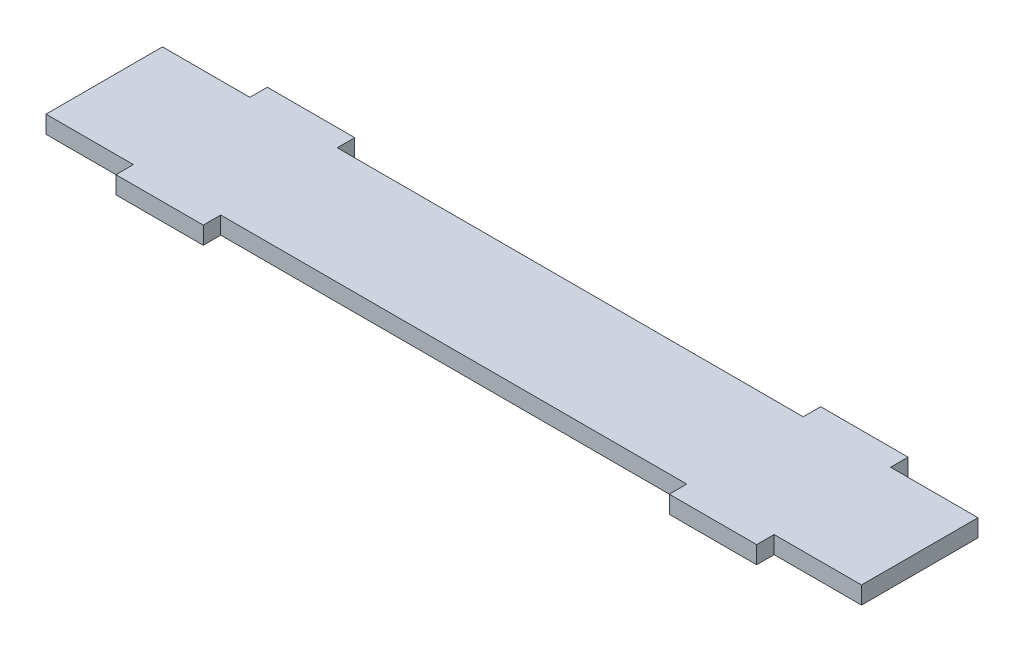
SolidWorks part; units mm, degrees
ref_plane "前视基准面" through (0, 0, 0) normal (0, 0, 1) x (1, 0, 0)
ref_plane "上视基准面" through (0, 0, 0) normal (0, 1, 0) x (1, 0, 0)
ref_plane "右视基准面" through (0, 0, 0) normal (1, 0, 0) x (0, 0, -1)
other "Configuration Table"
sketch "草图1" plane through (0, 0, 0) normal (0, 1, 0) x (1, 0, 0)
  line L0 (0, 16.6337) -> (0, -14.7525) construction
  line L1 (-70, 10) -> (70, 10)
  line L2 (-70, 10) -> (-70, -10)
  line L3 (-70, -10) -> (70, -10)
  line L4 (70, 10) -> (70, -10)
  line L5 (-70, 10) -> (70, -10) construction
  line L6 (-70, -10) -> (70, 10) construction
  line L7 (-55, 10) -> (-40, 10)
  line L8 (-55, 10) -> (-55, 13)
  line L9 (-55, 13) -> (-40, 13)
  line L10 (-40, 10) -> (-40, 13)
  line L11 (40, 10) -> (40, 13)
  line L12 (55, 13) -> (40, 13)
  line L13 (55, 10) -> (55, 13)
  line L14 (55, 10) -> (40, 10)
  line L15 (-70, 0) -> (-35.2475, 0) construction
  line L16 (55, -10) -> (40, -10)
  line L17 (55, -10) -> (55, -13)
  line L18 (55, -13) -> (40, -13)
  line L19 (40, -10) -> (40, -13)
  line L20 (-40, -10) -> (-40, -13)
  line L21 (-55, -13) -> (-40, -13)
  line L22 (-55, -10) -> (-55, -13)
  line L23 (-55, -10) -> (-40, -10)
  point P0 (0, 0)
  dimension "D1" = 20
  dimension "D2" = 140
  dimension "D3" = 3
  dimension "D4" = 15
  dimension "D5" = 40
extrude "凸台-拉伸1" add sketch "草图1" along normal blind 3 contours L4 L1 L2 L3 | L1 L10 L9 L8 | L3 L22 L21 L20 | L1 L13 L12 L11 | L18 L19 L16 L17
